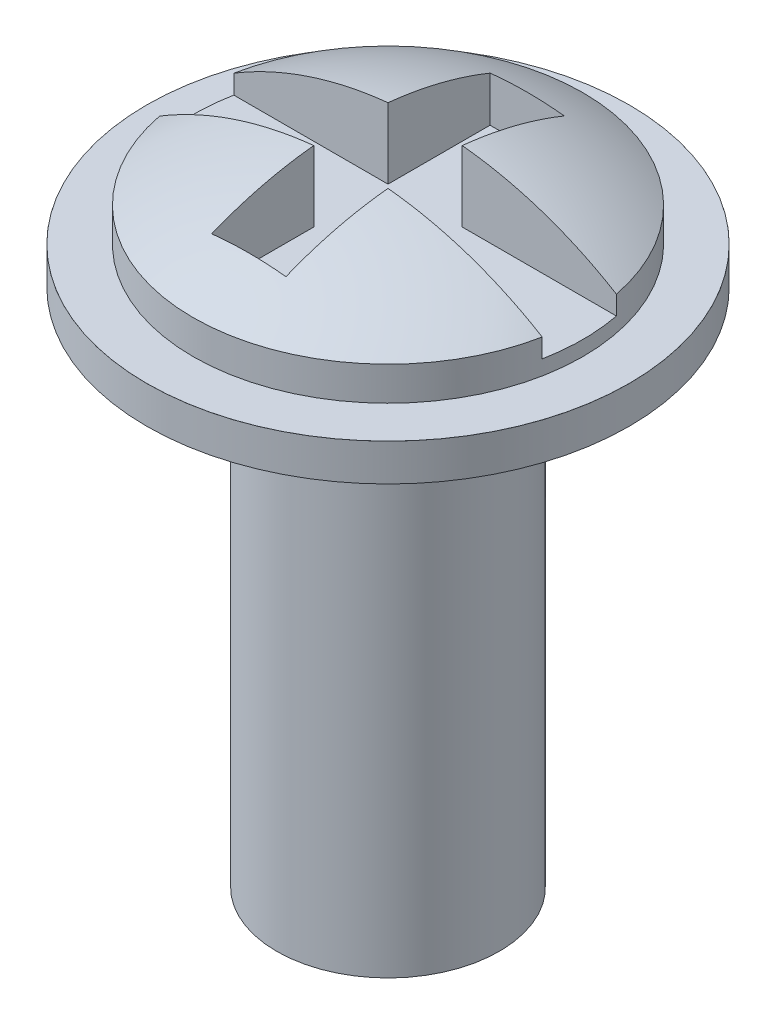
SolidWorks part; units mm, degrees
ref_plane "前视基准面" through (0, 0, 0) normal (0, 0, 1) x (1, 0, 0)
ref_plane "上视基准面" through (0, 0, 0) normal (0, 1, 0) x (1, 0, 0)
ref_plane "右视基准面" through (0, 0, 0) normal (1, 0, 0) x (0, 0, -1)
sketch "草图1" plane through (0, 0, 0) normal (0, 1, 0) x (1, 0, 0)
  circle A0 centre (0, 0) radius 1.5
  dimension "D1" = 3
extrude "拉伸1" add sketch "草图1" along normal blind 7
sketch "草图6" plane through (0, 7, 0) normal (0, 1, 0) x (1, 0, 0)
  circle A0 centre (0, 0) radius 3.25
  dimension "D1" = 6.5
extrude "凸台-拉伸1" add sketch "草图6" along normal blind 0.5
sketch "草图2" plane through (0, 7.5, 0) normal (0, 1, 0) x (-1, 0, 0)
  circle A0 centre (0, 0) radius 2.625
  dimension "D1" = 5.25
extrude "拉伸2" add sketch "草图2" along normal blind 1.2
sketch "草图3" plane through (0, 8.7, 0) normal (0, 1, 0) x (-1, 0, 0)
  line L0 (4.0624, 0) -> (-4.2778, 0) construction
  line L1 (0, -3.5166) -> (0, 3.738) construction
  line L3 (3.5023, -0.5) -> (-3.5023, -0.5)
  line L4 (3.5023, -0.5) -> (3.5023, 0.5)
  line L5 (3.5023, 0.5) -> (-3.5023, 0.5)
  line L6 (-3.5023, -0.5) -> (-3.5023, 0.5)
  dimension "D1" = 1
extrude "切除-拉伸1" cut sketch "草图3" against normal blind 1
sketch "草图4" plane through (0, 8.7, 0) normal (0, 1, 0) x (-1, 0, 0)
  line L0 (0, -3.8639) -> (0, 3.6765) construction
  line L1 (1.7727, 0) -> (-1.7019, 0) construction
  line L2 (0.5, -1.875) -> (-0.5, -1.875)
  line L3 (0.5, -1.875) -> (0.5, 1.875)
  line L4 (0.5, 1.875) -> (-0.5, 1.875)
  line L5 (-0.5, -1.875) -> (-0.5, 1.875)
  dimension "D1" = 1
  dimension "D2" = 3.75
extrude "切除-拉伸2" cut sketch "草图4" against normal blind 1
sketch "草图5" plane through (0, 0, 0) normal (1, 0, 0) x (0, 0, -1)
  line L0 (0, -2.1059) -> (0, 12.2815) construction
  line L1 (-0.5, 8.7) -> (-2.625, 8.7) construction
  line L2 (0, 11.3241) -> (-3.6858, 11.3241)
  line L3 (-3.6858, 7.0786) -> (-3.6858, 11.3241)
  line L5 (0, 11.3241) -> (0, 8.7)
  arc A2 (0, 8.7) -> (-3.6858, 7.0786) centre (0, 3.7) ccw
  dimension "D1" = 5
revolve "切除-旋转16" cut sketch "草图5" angle 360 about L0
